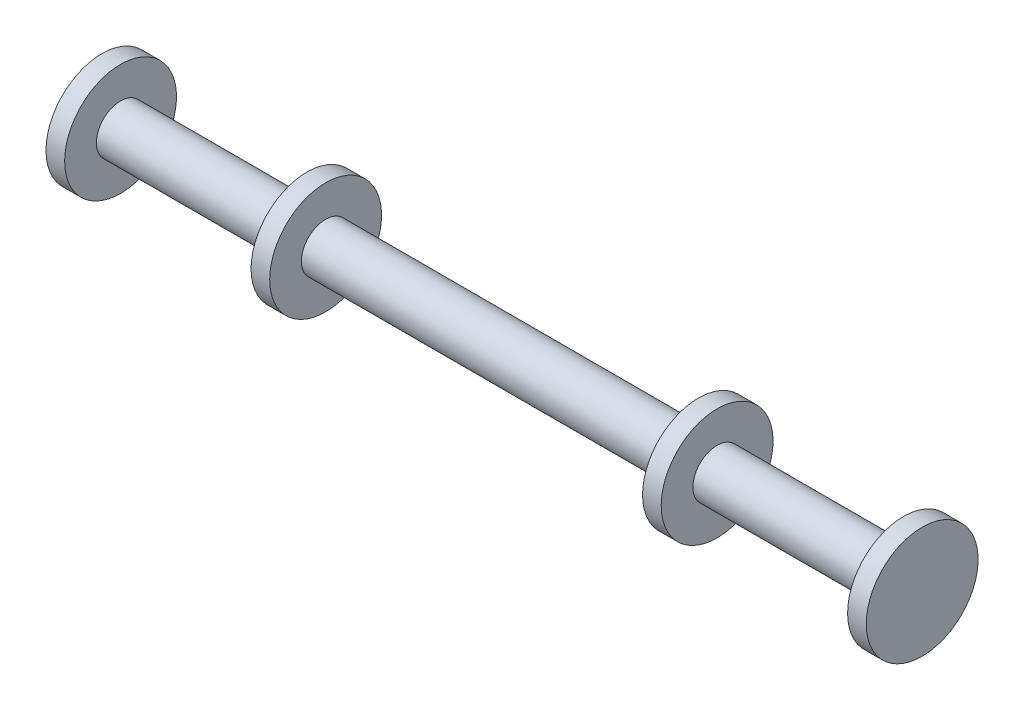
SolidWorks part; units mm, degrees
ref_plane "Front Plane" through (0, 0, 0) normal (0, 0, 1) x (1, 0, 0)
ref_plane "Top Plane" through (0, 0, 0) normal (0, 1, 0) x (1, 0, 0)
ref_plane "Right Plane" through (0, 0, 0) normal (1, 0, 0) x (0, 0, -1)
sketch "Sketch1" plane through (0, 0, 0) normal (0, 0, 1) x (1, 0, 0)
  line L1 (-55.88, 3.302) -> (55.88, 3.302)
  line L2 (-55.88, 3.302) -> (-55.88, 0)
  line L3 (-55.88, 0) -> (55.88, 0)
  line L4 (55.88, 3.302) -> (55.88, 0)
  line L5 (55, 0) -> (-55, 0) construction
  line L6 (0, -55) -> (0, 55) construction
  line L7 (-55.88, 0) -> (55.88, 0) construction
  point P4 (0, 3.302)
  dimension "D1" = 3.302
  dimension "D2" = 111.76
revolve "Revolve1" add sketch "Sketch1" angle 360 about L7
sketch "Sketch6" plane through (0, 0, 0) normal (0, 0, 1) x (1, 0, 0)
  line L0 (-27.94, 3.302) -> (-27.94, 7.62)
  line L1 (55.88, 3.302) -> (-55.88, 3.302) construction
  line L2 (-27.94, 7.62) -> (-25.4, 7.62)
  line L3 (-25.4, 7.62) -> (-25.4, 3.302)
  line L4 (-25.4, 3.302) -> (-27.94, 3.302)
  line L5 (0, -55) -> (0, 55) construction
  line L6 (-31.8784, 0) -> (55.88, 0) construction
  line L7 (27.94, 3.302) -> (25.4, 3.302)
  line L8 (27.94, 3.302) -> (27.94, 7.62)
  line L9 (27.94, 7.62) -> (25.4, 7.62)
  line L10 (25.4, 3.302) -> (25.4, 7.62)
  line L11 (55, 0) -> (-55, 0) construction
  line L12 (55.88, -3.302) -> (55.88, 3.302) construction
  line L13 (55.88, 3.302) -> (-55.88, 3.302) construction
  line L14 (-53.34, 3.302) -> (-55.88, 3.302)
  line L15 (-53.34, 3.302) -> (-53.34, 7.62)
  line L16 (-53.34, 7.62) -> (-55.88, 7.62)
  line L17 (-55.88, 3.302) -> (-55.88, 7.62)
  line L19 (53.34, 3.302) -> (55.88, 3.302)
  line L20 (53.34, 3.302) -> (53.34, 7.62)
  line L21 (53.34, 7.62) -> (55.88, 7.62)
  line L22 (55.88, 3.302) -> (55.88, 7.62)
  dimension "D1" = 25.4
  dimension "D2" = 2.54
  dimension "D3" = 4.318
  dimension "D4" = 25.4
  dimension "D5" = 2.54
  dimension "D6" = 4.318
  dimension "D7" = 4.318
  dimension "D8" = 2.54
  dimension "D9" = 25.4
  dimension "D10" = 4.318
  dimension "D11" = 2.54
  dimension "D12" = 25.4
revolve "Revolve2" add sketch "Sketch6" angle 360 about L6
